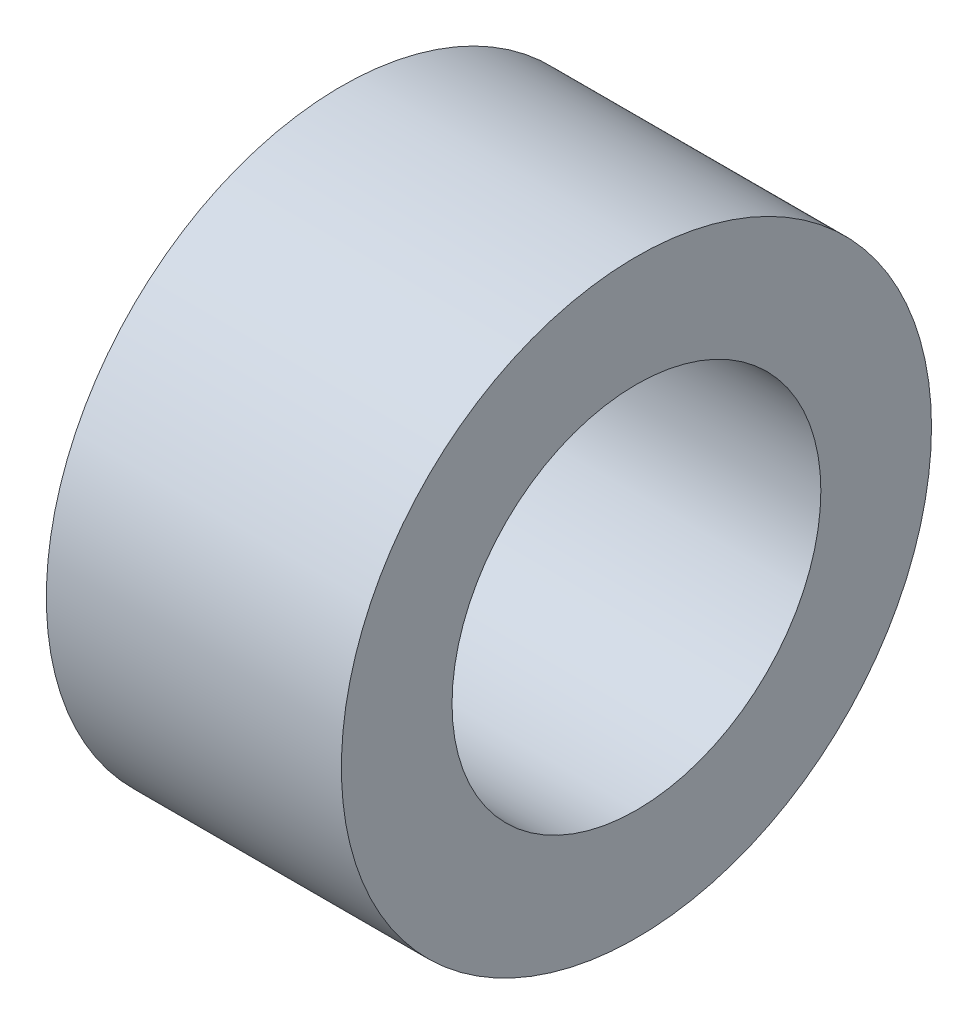
SolidWorks part; units mm, degrees
ref_plane "Front Plane" through (0, 0, 0) normal (0, 0, 1) x (1, 0, 0)
ref_plane "Top Plane" through (0, 0, 0) normal (0, 1, 0) x (1, 0, 0)
ref_plane "Right Plane" through (0, 0, 0) normal (1, 0, 0) x (0, 0, -1)
sketch "Sketch1" plane through (0, 0, 0) normal (1, 0, 0) x (0, 0, -1)
  circle A0 centre (0, 0) radius 5
  circle A1 centre (0, 0) radius 3.125
  dimension "D1" = 6.25
  dimension "D2" = 10
extrude "Boss-Extrude1" add sketch "Sketch1" along normal mid plane 5
